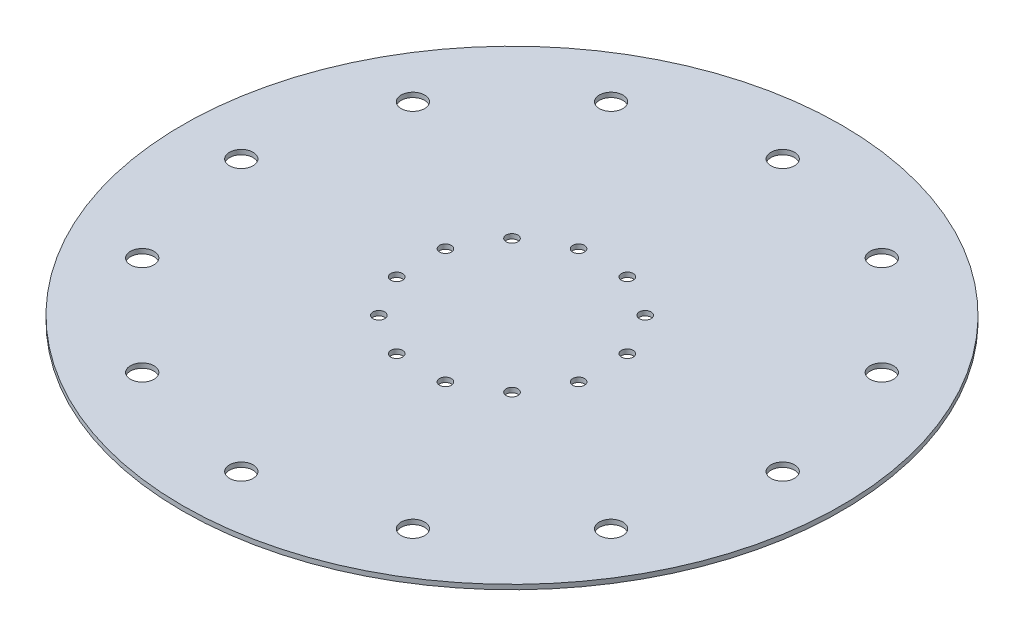
SolidWorks part; units mm, degrees
ref_plane "Front Plane" through (0, 0, 0) normal (0, 0, 1) x (1, 0, 0)
ref_plane "Top Plane" through (0, 0, 0) normal (0, 1, 0) x (1, 0, 0)
ref_plane "Right Plane" through (0, 0, 0) normal (1, 0, 0) x (0, 0, -1)
sketch "Sketch1" plane through (0, 0, 0) normal (0, 1, 0) x (1, 0, 0)
  line L0 (0, -1000) -> (0, 49000) construction
  line L1 (-1000, 0) -> (49000, 0) construction
  line L2 (-866.0254, 500) -> (42435.2448, -24500) construction
  line L3 (-707.1068, -707.1068) -> (34648.2323, 34648.2323) construction
  line L4 (-707.1068, 707.1068) -> (34648.2323, -34648.2323) construction
  line L5 (-866.0254, -500) -> (42435.2448, 24500) construction
  line L6 (-500, -866.0254) -> (24500, 42435.2448) construction
  line L7 (-500, 866.0254) -> (24500, -42435.2448) construction
  line L8 (-965.9258, -258.819) -> (47330.3655, 12682.1332) construction
  line L9 (-965.9258, 258.819) -> (47330.3655, -12682.1332) construction
  line L10 (-258.819, -965.9258) -> (12682.1332, 47330.3655) construction
  line L11 (-258.819, 965.9258) -> (12682.1332, -47330.3655) construction
  circle A0 centre (0, 0) radius 140
  circle A1 centre (-99.5929, 57.5) radius 5
  circle A3 centre (-57.5, 99.5929) radius 5
  circle A6 centre (57.5, 99.5929) radius 5
  circle A7 centre (99.5929, 57.5) radius 5
  circle A13 centre (99.5929, -57.5) radius 5
  circle A14 centre (57.5, -99.5929) radius 5
  circle A15 centre (-57.5, -99.5929) radius 5
  circle A16 centre (-99.5929, -57.5) radius 5
  circle A17 centre (0, 115) radius 5
  circle A20 centre (0, -115) radius 5
  circle A21 centre (-115, 0) radius 5
  circle A24 centre (115, 0) radius 5
  circle A25 centre (-10.3528, 38.637) radius 2.5
  circle A26 centre (-28.2843, 28.2843) radius 2.5
  circle A27 centre (-38.637, 10.3528) radius 2.5
  circle A28 centre (-38.637, -10.3528) radius 2.5
  circle A29 centre (38.637, -10.3528) radius 2.5
  circle A30 centre (38.637, 10.3528) radius 2.5
  circle A31 centre (28.2843, 28.2843) radius 2.5
  circle A32 centre (10.3528, 38.637) radius 2.5
  circle A33 centre (28.2843, -28.2843) radius 2.5
  circle A34 centre (-28.2843, -28.2843) radius 2.5
  circle A35 centre (10.3528, -38.637) radius 2.5
  circle A36 centre (-10.3528, -38.637) radius 2.5
  dimension "D1" = 280
  dimension "D4" = 5
  dimension "D5" = 115
  dimension "D7" = 10
  dimension "D8" = 10
  dimension "D9" = 5
  dimension "D10" = 10
  dimension "D11" = 5
  dimension "D12" = 5
  dimension "D13" = 115
  dimension "D14" = 10
  dimension "D16" = 10
  dimension "D17" = 40
  dimension "D18" = 40
  dimension "D19" = 40
  dimension "D21" = 40
  dimension "D2" = 30
  dimension "D3" = 30
  dimension "D6" = 115
  dimension "D15" = 115
  dimension "D20" = 30
extrude "Boss-Extrude1" add sketch "Sketch1" along normal blind 2
